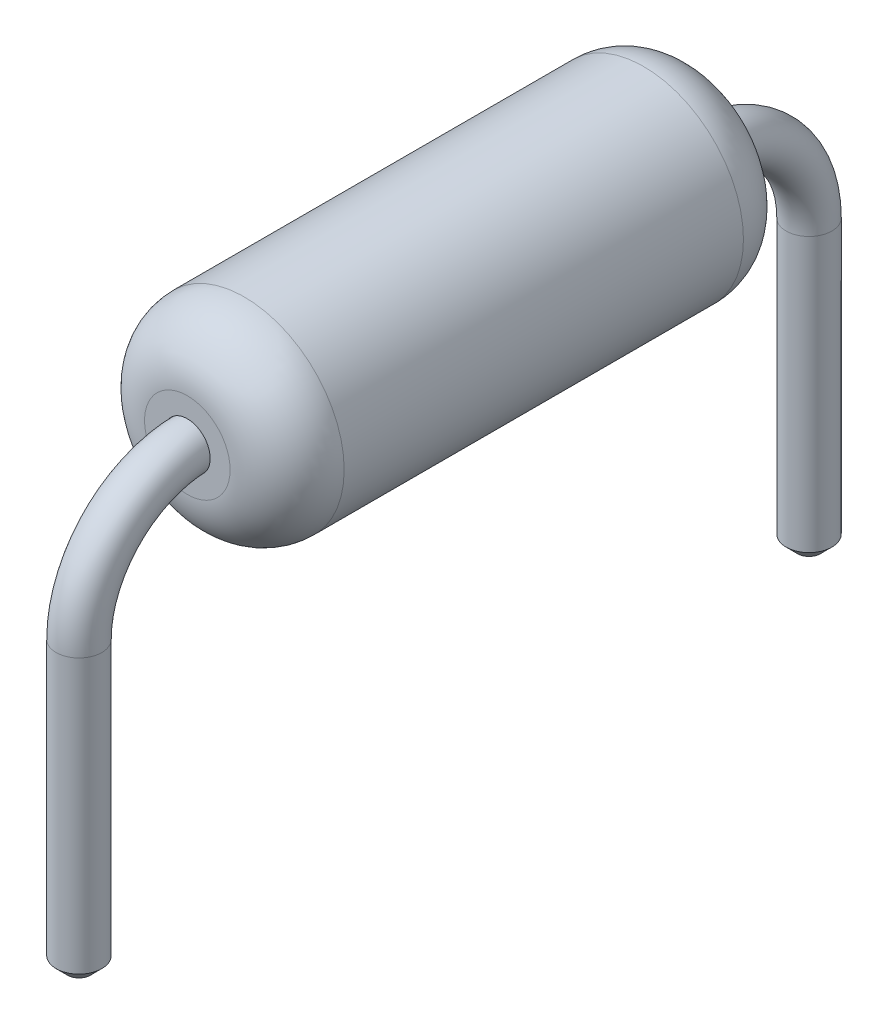
SolidWorks part; units mm, degrees
ref_plane "Front Plane" through (0, 0, 0) normal (0, 0, 1) x (1, 0, 0)
ref_plane "Top Plane" through (0, 0, 0) normal (0, 1, 0) x (1, 0, 0)
ref_plane "Right Plane" through (0, 0, 0) normal (1, 0, 0) x (0, 0, -1)
sketch "Sketch1" plane through (0, 0, 0) normal (1, 0, 0) x (0, 0, -1)
  line L0 (-6.4, -3) -> (-6.4, 2)
  line L1 (-4.4, 4) -> (4.4, 4)
  line L2 (6.4, 2) -> (6.4, -3)
  arc A0 (-6.4, 2) -> (-4.4, 4) centre (-4.4, 2) cw
  arc A1 (4.4, 4) -> (6.4, 2) centre (4.4, 2) cw
  point P10 (0, 4)
  dimension "D3" = 2
  dimension "D1" = 3
  dimension "D2" = 4
  dimension "D4" = 12.8
ref_plane "Plane1" through (0, -3, 6.4) normal (0, 1, 0) x (1, 0, 0)
sketch "Sketch6" plane through (0, -3, 6.4) normal (0, 1, 0) x (1, 0, 0)
  circle A0 centre (0, 0) radius 0.4
  dimension "D1" = 0.8
sweep "Sweep1" add profiles "Sketch6" path "Sketch1"
sketch "Sketch7" plane through (0, 0, 0) normal (0, 0, 1) x (1, 0, 0)
  circle A0 centre (0, 4) radius 0.4 construction
  circle A1 centre (0, 4) radius 0.4
  circle A2 centre (0, 4) radius 1.75
  dimension "D1" = 3.5
extrude "Boss-Extrude1" add sketch "Sketch7" along normal mid plane 9 separate body
fillet "Fillet1" radius 1 2 edges at (1.75, 4, -4.5) (1.75, 4, 4.5)
chamfer "Chamfer1" distance 0.2 angle 45 2 edges at (0, -3, 6.8) (0, -3, -6.8)
